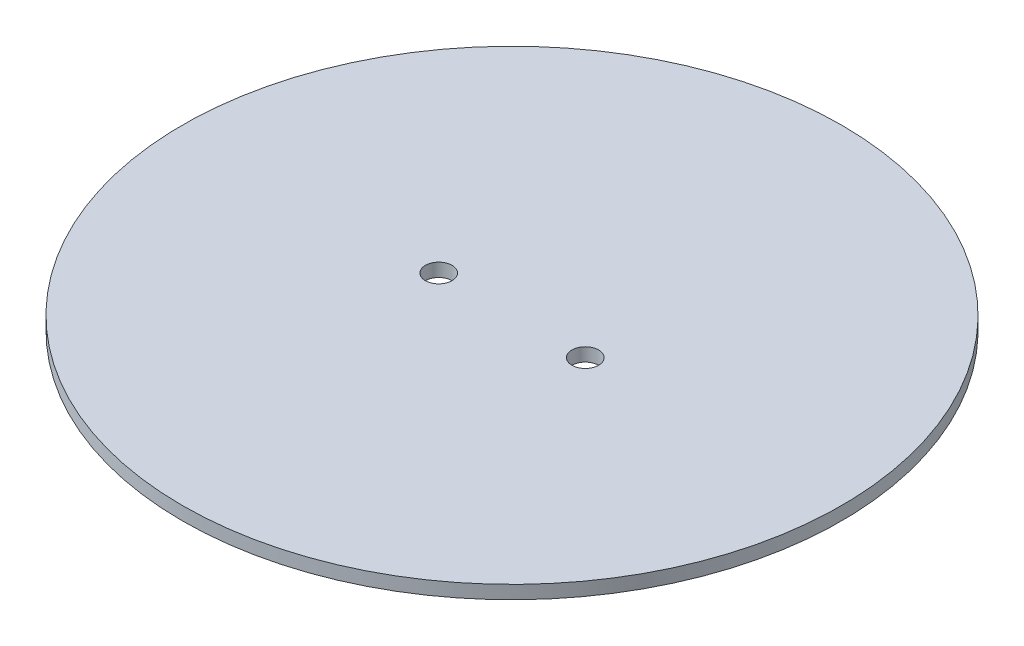
SolidWorks part; units mm, degrees
ref_plane "Front Plane" through (0, 0, 0) normal (0, 0, 1) x (1, 0, 0)
ref_plane "Top Plane" through (0, 0, 0) normal (0, 1, 0) x (1, 0, 0)
ref_plane "Right Plane" through (0, 0, 0) normal (1, 0, 0) x (0, 0, -1)
sketch "Sketch1" plane through (0, 0, 0) normal (0, 1, 0) x (1, 0, 0)
  circle A0 centre (0, 0) radius 74.2
  circle A1 centre (-16.5, 0) radius 3
  circle A2 centre (16.5, 0) radius 3
  dimension "D1" = 148.4
  dimension "D2" = 6
  dimension "D3" = 6
  dimension "D4" = 16.5
  dimension "D5" = 16.5
extrude "Boss-Extrude1" add sketch "Sketch1" along normal blind 3
